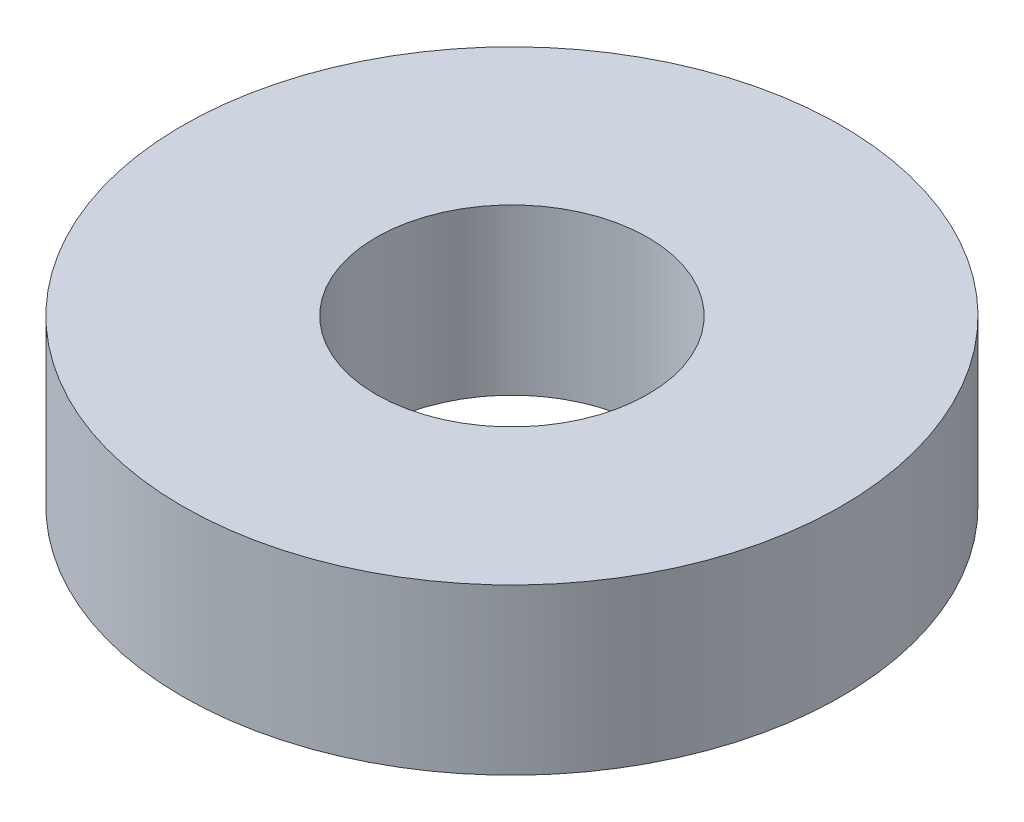
SolidWorks part; units mm, degrees
ref_plane "Front Plane" through (0, 0, 0) normal (0, 0, 1) x (1, 0, 0)
ref_plane "Top Plane" through (0, 0, 0) normal (0, 1, 0) x (1, 0, 0)
ref_plane "Right Plane" through (0, 0, 0) normal (1, 0, 0) x (0, 0, -1)
sketch "Sketch2" plane through (0, 0, 0) normal (0, 1, 0) x (1, 0, 0)
  circle A0 centre (0, 0) radius 4
  circle A1 centre (0, 0) radius 1.65
  dimension "D1" = 8
  dimension "D2" = 3.3
extrude "Boss-Extrude1" add sketch "Sketch2" along normal blind 2
